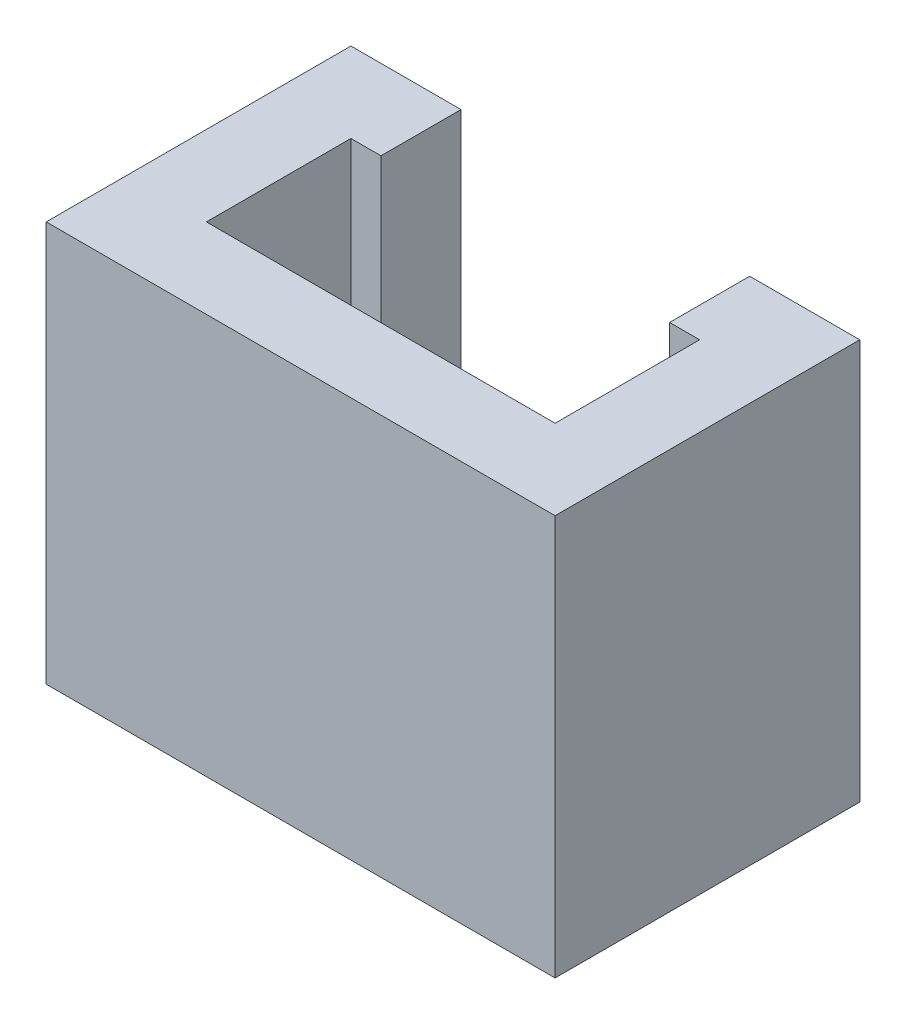
SolidWorks part; units mm, degrees
ref_plane "Front Plane" through (0, 0, 0) normal (0, 0, 1) x (1, 0, 0)
ref_plane "Top Plane" through (0, 0, 0) normal (0, 1, 0) x (1, 0, 0)
ref_plane "Right Plane" through (0, 0, 0) normal (1, 0, 0) x (0, 0, -1)
sketch "Sketch1" plane through (0, 0, 0) normal (0, 1, 0) x (1, 0, 0)
  line L0 (-8.71, 0) -> (8.71, 0)
  line L1 (8.71, 0) -> (8.71, 7.22)
  line L2 (8.71, 7.22) -> (7.21, 7.22)
  line L3 (0, 0) -> (0, 19.6218) construction
  line L4 (-8.71, 7.22) -> (-7.21, 7.22)
  line L5 (-8.71, 0) -> (-8.71, 7.22)
  line L6 (-12.71, 11.22) -> (-7.21, 11.22)
  line L7 (-12.71, -4) -> (-12.71, 11.22)
  line L8 (-12.71, -4) -> (12.71, -4)
  line L9 (12.71, -4) -> (12.71, 11.22)
  line L10 (12.71, 11.22) -> (7.21, 11.22)
  line L11 (-7.21, 7.22) -> (-7.21, 11.22)
  line L12 (7.21, 11.22) -> (7.21, 7.22)
  dimension "D1" = 8.71
  dimension "D2" = 7.22
  dimension "D3" = 4
  dimension "1.5" = 1.5
extrude "Boss-Extrude1" add sketch "Sketch1" along normal blind 20
